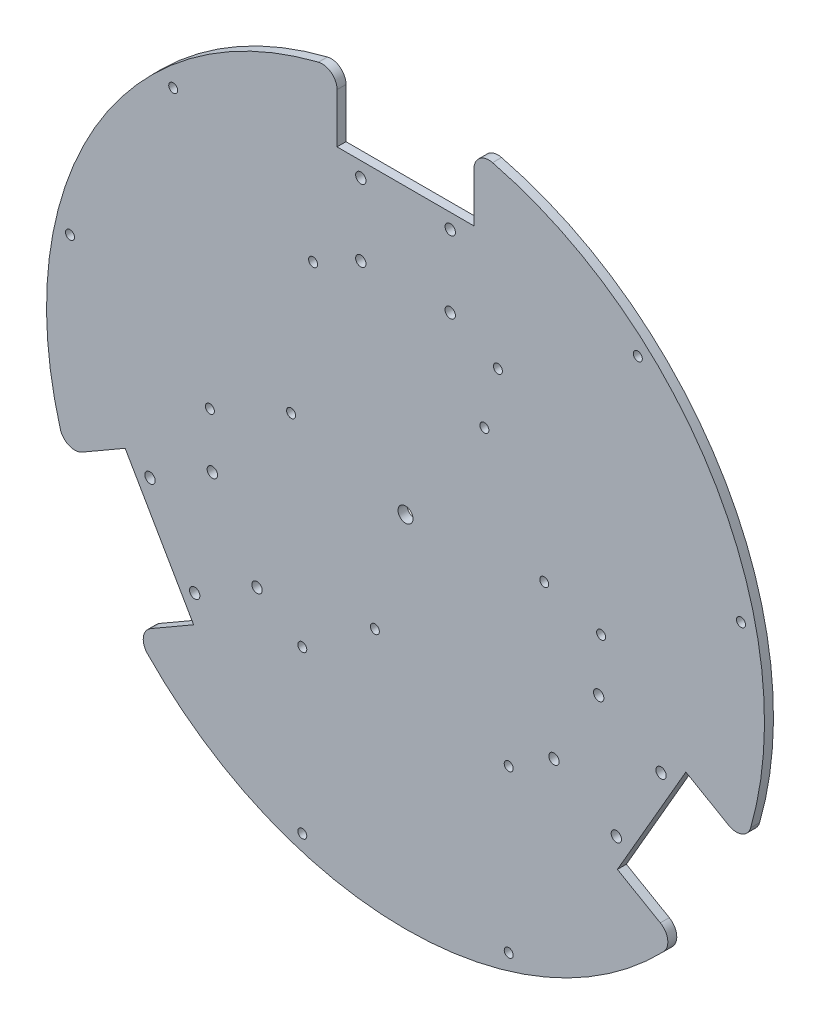
SolidWorks part; units mm, degrees
ref_plane "Front Plane" through (0, 0, 0) normal (0, 0, 1) x (1, 0, 0)
ref_plane "Top Plane" through (0, 0, 0) normal (0, 1, 0) x (1, 0, 0)
ref_plane "Right Plane" through (0, 0, 0) normal (1, 0, 0) x (0, 0, -1)
sketch "Sketch1" plane through (0, 0, 0) normal (0, 0, 1) x (1, 0, 0)
  line L0 (2.3607, 103.329) -> (-74.2418, -29.3505)
  line L1 (-74.2418, -29.3505) -> (-54.2418, -63.9915)
  line L2 (-54.2418, -63.9915) -> (98.9633, -63.9915)
  line L3 (98.9633, -63.9915) -> (118.9633, -29.3505)
  line L4 (118.9633, -29.3505) -> (42.3607, 103.329)
  line L5 (42.3607, 103.329) -> (2.3607, 103.329)
  circle A0 centre (7.4157, 93.329) radius 1.73
  circle A1 centre (37.3057, 93.329) radius 1.73
  circle A2 centre (37.3057, 69.269) radius 1.73
  circle A3 centre (7.4157, 69.269) radius 1.73
  circle A4 centre (107.7755, -28.7283) radius 1.73
  circle A5 centre (86.939, -16.6983) radius 1.73
  circle A6 centre (71.994, -42.5838) radius 1.73
  circle A7 centre (92.8305, -54.6138) radius 1.73
  circle A8 centre (-42.2175, -16.6983) radius 1.73
  circle A9 centre (-27.2725, -42.5838) radius 1.73
  circle A10 centre (-63.0541, -28.7283) radius 1.73
  circle A11 centre (-48.1091, -54.6138) radius 1.73
  circle A12 centre (22.3607, 3.329) radius 2.5
extrude "Boss-Extrude2" add sketch "Sketch1" along normal blind 3
sketch "Sketch2" plane through (0, 0, 3) normal (0, 0, 1) x (1, 0, 0)
  line L0 (7.4157, 103.329) -> (7.4157, 98.329)
  line L1 (42.3607, 103.329) -> (2.3607, 103.329) construction
  line L2 (7.4157, 98.329) -> (45.2475, 98.329)
  line L3 (118.9633, -29.3505) -> (42.3607, 103.329) construction
  line L4 (45.2475, 98.329) -> (42.3607, 103.329)
  line L5 (42.3607, 103.329) -> (2.3607, 103.329)
  line L6 (2.3607, 103.329) -> (-0.526, 98.329)
  line L7 (2.3607, 103.329) -> (-74.2418, -29.3505) construction
  line L8 (-0.526, 98.329) -> (7.4157, 98.329)
  line L9 (118.9633, -29.3505) -> (114.6331, -26.8505)
  line L10 (114.6331, -26.8505) -> (116.0765, -24.3505)
  line L11 (116.0765, -24.3505) -> (118.9633, -29.3505)
  line L12 (114.6331, -26.8505) -> (93.1898, -63.9915)
  line L13 (-54.2418, -63.9915) -> (98.9633, -63.9915) construction
  line L14 (93.1898, -63.9915) -> (98.9633, -63.9915)
  line L15 (98.9633, -63.9915) -> (118.9633, -29.3505)
  line L16 (-74.2418, -29.3505) -> (-69.9117, -26.8505)
  line L17 (-69.9117, -26.8505) -> (-48.4683, -63.9915)
  line L18 (-48.4683, -63.9915) -> (-54.2418, -63.9915)
  line L19 (-54.2418, -63.9915) -> (-74.2418, -29.3505)
  line L20 (-69.9117, -26.8505) -> (-71.3551, -24.3505)
  line L21 (-71.3551, -24.3505) -> (-74.2418, -29.3505)
  line M7 (42.3607, 103.329) -> (2.3607, 103.329)
  line M8 (2.3607, 103.329) -> (-74.2418, -29.3505)
  line M9 (-74.2418, -29.3505) -> (-54.2418, -63.9915)
  line M10 (-54.2418, -63.9915) -> (98.9633, -63.9915)
  line M11 (98.9633, -63.9915) -> (118.9633, -29.3505)
  line M12 (118.9633, -29.3505) -> (42.3607, 103.329)
extrude "Cut-Extrude1" cut sketch "Sketch2" against normal blind 10 contours L16 L20 M8 | L17 L16 M9 M10 | L9 L12 M10 M11 | L10 L9 M12 | L8 L0 M8 M7 | L0 L2 M12 M7
sketch "Sketch4" plane through (0, 0, 3) normal (0, 0, 1) x (1, 0, 0)
  line L0 (22.3607, 3.329) -> (58.7338, 24.329)
  line L1 (22.3607, 3.329) -> (-1.888, -10.671)
  line L2 (58.7338, 24.329) -> (68.7338, 7.0085)
  line L3 (-1.888, -10.671) -> (12.112, -34.9197)
  circle A0 centre (12.112, -34.9197) radius 1.5
  circle A1 centre (68.7338, 7.0085) radius 1.5
  circle A2 centre (48.7338, 41.6495) radius 1.5
  circle A3 centre (-15.888, 13.5777) radius 1.5
extrude "Cut-Extrude2" cut sketch "Sketch4" against normal through all
sketch "Sketch5" plane through (0, 0, 3) normal (0, 0, 1) x (1, 0, 0)
  line L0 (-0.526, 98.329) -> (-0.526, 121.129)
  line L1 (45.2475, 98.329) -> (45.2475, 121.129)
  line L2 (-71.3551, -24.3505) -> (-91.1004, -35.7505)
  line L3 (-48.4683, -63.9915) -> (-68.2137, -75.3915)
  line L4 (116.0765, -24.3505) -> (135.8219, -35.7505)
  line L5 (93.1898, -63.9915) -> (112.9352, -75.3915)
  line L9 (-0.526, 98.329) -> (45.2475, 98.329)
  line L10 (45.2475, 98.329) -> (116.0765, -24.3505)
  line L11 (116.0765, -24.3505) -> (93.1898, -63.9915)
  line L12 (93.1898, -63.9915) -> (-48.4683, -63.9915)
  line L13 (-48.4683, -63.9915) -> (-71.3551, -24.3505)
  line L14 (-71.3551, -24.3505) -> (-0.526, 98.329)
  circle A0 centre (22.3607, 3.329) radius 120.0027
  line M5 (-48.4683, -63.9915) -> (93.1898, -63.9915)
  line M7 (116.0765, -24.3505) -> (45.2475, 98.329)
  line M9 (-0.526, 98.329) -> (-71.3551, -24.3505)
extrude "Boss-Extrude3" add sketch "Sketch5" against normal blind 3 contours L4 A0 L1 M7 | L0 A0 L2 M9 | L3 A0 L5 M5
fillet "Fillet1" radius 5 6 edges at (-0.526, 121.129, 1.5) (45.2475, 121.129, 1.5) (-68.2137, -75.3915, 1.5) (-91.1004, -35.7505, 1.5) (112.9352, -75.3915, 1.5) (135.8219, -35.7505, 1.5)
sketch "Sketch6" plane through (0, 0, 0) normal (0, 0, -1) x (-1, 0, 0)
  line L0 (-22.3607, 3.329) -> (72.5451, 58.1229)
  line L1 (72.5451, 58.1229) -> (89.7951, 28.245)
  line L2 (89.7951, 28.245) -> (72.5451, 58.1229)
  line L3 (89.7951, 28.245) -> (66.4125, 14.745)
  line L4 (72.5451, 58.1229) -> (49.1625, 44.6229)
  line L5 (66.4125, 14.745) -> (49.1625, 44.6229)
  line L6 (-22.3607, 3.329) -> (-22.3607, 98.329)
  line L7 (0.526, 98.329) -> (-45.2475, 98.329) construction
  line L8 (-22.3607, 3.329) -> (59.9117, -44.171)
  line L9 (48.4683, -63.9915) -> (71.3551, -24.3505) construction
  circle A2 centre (89.7951, 28.245) radius 1.5
  circle A3 centre (55.2951, 88.0008) radius 1.5
  circle A4 centre (43.0298, 1.245) radius 1.5
  circle A5 centre (8.5298, 61.0008) radius 1.5
  circle A6 centre (12.1393, -106.2589) radius 1.5
  circle A7 centre (12.1393, -52.2589) radius 1.5
  circle A8 centre (-56.8607, -106.2589) radius 1.5
  circle A9 centre (-56.8607, -52.2589) radius 1.5
  circle A10 centre (-100.0166, 88.0008) radius 1.5
  circle A11 centre (-134.5166, 28.245) radius 1.5
  circle A12 centre (-87.7512, 1.245) radius 1.5
  circle A13 centre (-53.2512, 61.0008) radius 1.5
extrude "Cut-Extrude3" cut sketch "Sketch6" against normal through all contours L3 A2 L2 | L2 A2 L3 | A4 | A5 | A3 | A10 | A13 | A11 | A12 | A9 | A7 | A8 | A6
sketch "Sketch7" plane through (0, 0, 0) normal (0, 0, -1) x (-1, 0, 0)
  line L0 (-37.3057, 93.329) -> (-7.4157, 93.329)
  line L1 (-22.3607, 93.329) -> (-22.3607, 3.329)
  line L2 (-7.4157, 69.269) -> (-22.3607, 69.269)
  line L3 (-37.3057, 69.269) -> (-22.3607, 69.269)
  line L4 (-45.2475, 98.329) -> (0.526, 98.329)
  line L5 (0.526, 98.329) -> (0.526, 121.129)
  line L6 (-45.2475, 98.329) -> (-45.2475, 121.129)
  line L7 (71.3551, -24.3505) -> (48.4683, -63.9915)
  line L8 (48.4683, -63.9915) -> (68.2137, -75.3915)
  line L9 (68.2137, -75.3915) -> (91.1004, -35.7505)
  line L10 (91.1004, -35.7505) -> (71.3551, -24.3505)
  line L11 (-45.2475, 121.129) -> (0.526, 121.129)
  line L12 (-116.0765, -24.3505) -> (-93.1898, -63.9915)
  line L13 (-93.1898, -63.9915) -> (-112.9352, -75.3915)
  line L14 (-116.0765, -24.3505) -> (-135.8219, -35.7505)
  line L15 (-135.8219, -35.7505) -> (-112.9352, -75.3915)
  line L16 (-37.3057, 93.329) -> (-37.3057, 69.269)
  line L17 (-7.4157, 69.269) -> (-7.4157, 93.329)
  circle A0 centre (15.888, 13.5777) radius 1.5
  circle A1 centre (-12.112, -34.9197) radius 1.5
  circle A2 centre (-68.7338, 7.0085) radius 1.5
  circle A3 centre (-48.7338, 41.6495) radius 1.5
  circle A4 centre (-100.0166, 88.0008) radius 1.5
  circle A5 centre (-53.2512, 61.0008) radius 1.5
  circle A6 centre (-134.5166, 28.245) radius 1.5
  circle A7 centre (-87.7512, 1.245) radius 1.5
  circle A8 centre (55.2951, 88.0008) radius 1.5
  circle A9 centre (8.5298, 61.0008) radius 1.5
  circle A10 centre (89.7951, 28.245) radius 1.5
  circle A11 centre (43.0298, 1.245) radius 1.5
  circle A12 centre (12.1393, -52.2589) radius 1.5
  circle A13 centre (12.1393, -106.2589) radius 1.5
  circle A14 centre (-56.8607, -106.2589) radius 1.5
  circle A15 centre (-56.8607, -52.2589) radius 1.5
  circle A24 centre (-37.3057, 93.329) radius 1.73
  circle A25 centre (-7.4157, 93.329) radius 1.73
  circle A26 centre (-7.4157, 69.269) radius 1.73
  circle A27 centre (-37.3057, 69.269) radius 1.73
  circle A28 centre (-22.3607, 3.329) radius 120.0027
